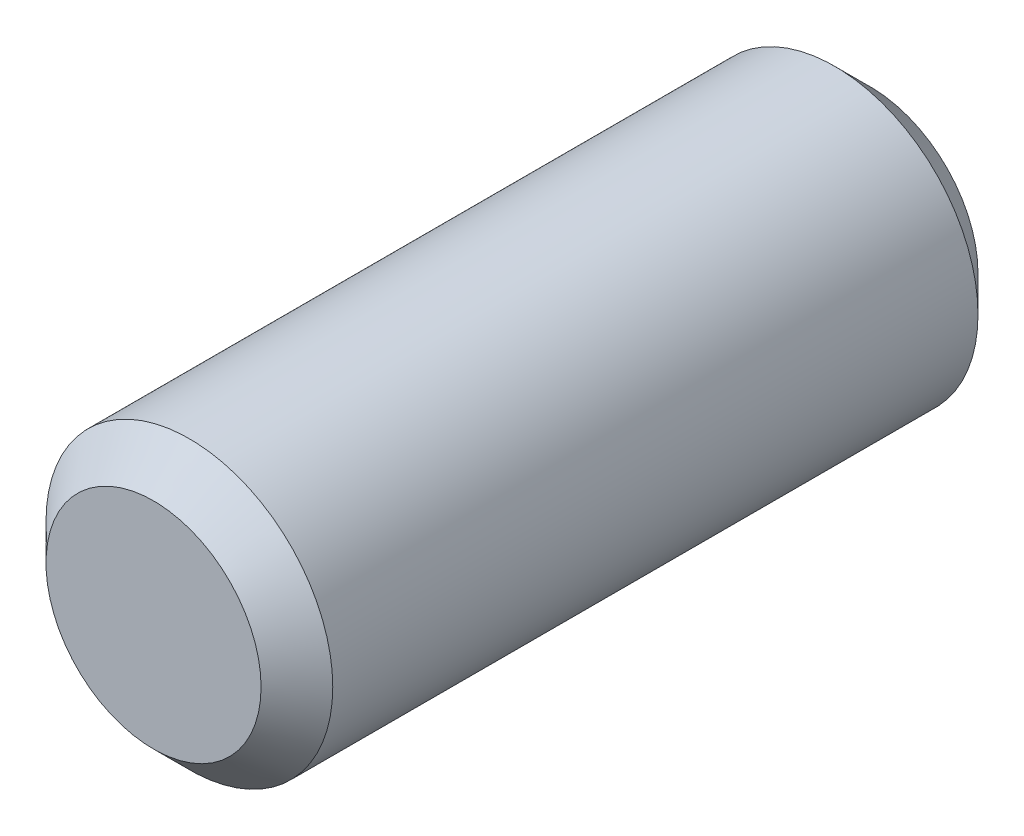
SolidWorks part; units mm, degrees
ref_plane "Plano frontal" through (0, 0, 0) normal (0, 0, 1) x (1, 0, 0)
ref_plane "Plano superior" through (0, 0, 0) normal (0, 1, 0) x (1, 0, 0)
ref_plane "Plano direito" through (0, 0, 0) normal (1, 0, 0) x (0, 0, -1)
sketch "Esboço1" plane through (0, 0, 0) normal (0, 0, 1) x (1, 0, 0)
  circle A0 centre (208.8814, 179.8739) radius 4
  dimension "D1" = 8
extrude "Ressalto-extrusão1" add sketch "Esboço1" against normal up to surface (20 mm away)
chamfer "Chanfro1" distance 1 angle 45 2 edges at (212.8814, 179.8739, -20) (212.8814, 179.8739, 0)
